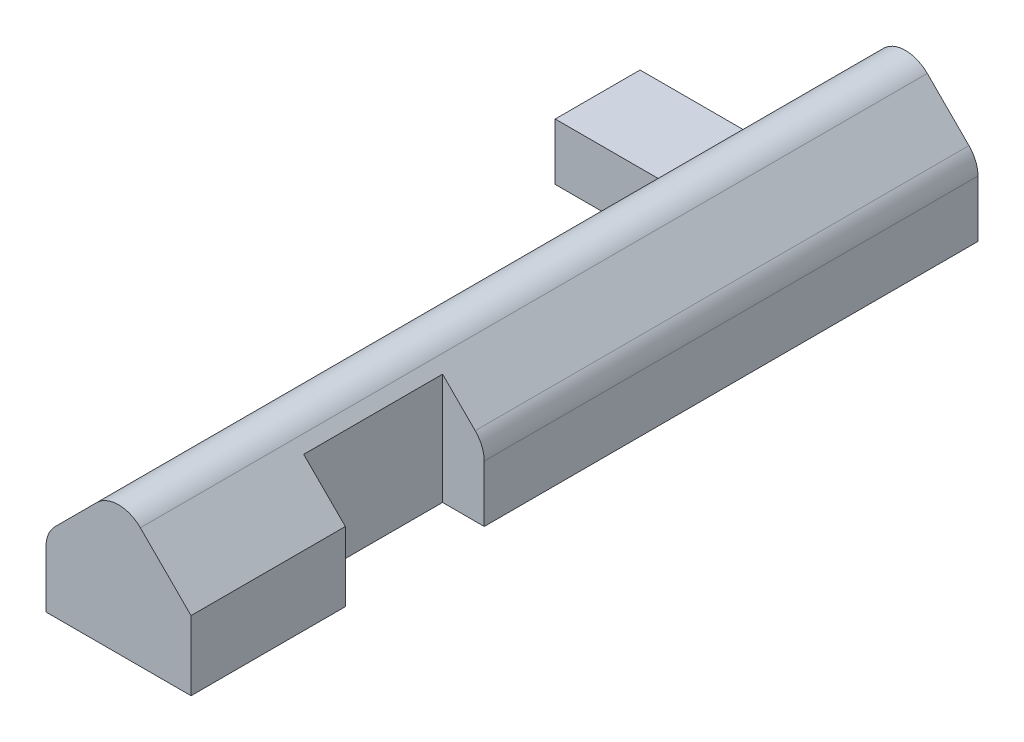
SolidWorks part; units mm, degrees
ref_plane "Płaszczyzna przednia" through (0, 0, 0) normal (0, 0, 1) x (1, 0, 0)
ref_plane "Płaszczyzna górna" through (0, 0, 0) normal (0, 1, 0) x (1, 0, 0)
ref_plane "Płaszczyzna prawa" through (0, 0, 0) normal (1, 0, 0) x (0, 0, -1)
sketch "Szkic1" plane through (0, 0, 0) normal (0, 0, 1) x (1, 0, 0)
  line L0 (0, 0) -> (0, 9.4056) construction
  line L1 (-4.7, 2.25) -> (4.7, 2.25)
  line L2 (-4.7, 2.25) -> (-4.7, -2.25)
  line L3 (-4.7, -2.25) -> (4.7, -2.25)
  line L4 (4.7, 2.25) -> (4.7, -2.25)
  line L5 (-4.7, 2.25) -> (4.7, -2.25) construction
  line L6 (-4.7, -2.25) -> (4.7, 2.25) construction
  line L7 (-4.7, 2.25) -> (0, 6.95)
  line L8 (0, 6.95) -> (4.7, 2.25)
  point P0 (0, 0)
  dimension "D1" = 9.4
  dimension "D2" = 4.5
  dimension "D3" = 45
extrude "Dodanie-wyciągnięcie1" add sketch "Szkic1" along normal blind 51 contours L8 L7 L1 | L4 L1 L2 L3
sketch "Szkic2" plane through (0, -2.25, 0) normal (0, -1, 0) x (1, 0, 0)
  line L0 (0, 0) -> (0, 51) construction
  line L1 (-4.7, 0) -> (4.7, 0) construction
  line L2 (-4.7, 51) -> (4.7, 51) construction
  line L3 (2, 41) -> (2, 32)
  line L4 (0, 32) -> (10, 32)
  line L5 (0, 32) -> (0, 41)
  line L6 (0, 41) -> (10, 41)
  line L7 (10, 32) -> (10, 41)
  line M6 (4.7, 0) -> (4.7, 51)
  dimension "D1" = 10
  dimension "D2" = 9
  dimension "D3" = 32
  dimension "D4" = 2
extrude "Wytnij-wyciągnięcie1" cut sketch "Szkic2" against normal blind 10 contours L6 L3 L4 M6 | L4 L7 L6 M6
ref_plane "Płaszczyzna1" through (-22.5, 11.75, 5) normal (0, -1, 0) x (-1, 0, 0)
sketch "Szkic4" plane through (0, -2.25, 0) normal (0, -1, 0) x (1, 0, 0)
  line L0 (0, 0) -> (0, 5) construction
  line L2 (-4.7, 0) -> (4.7, 0) construction
  line L3 (0, 0) -> (0, -7.3747) construction
  line L9 (7.5, -5) -> (-7.5, -5)
  line L10 (7.5, -5) -> (7.5, 5)
  line L11 (7.5, 5) -> (-7.5, 5)
  line L12 (-7.5, -5) -> (-7.5, 5)
  line L13 (7.5, -5) -> (-7.5, 5) construction
  line L14 (7.5, 5) -> (-7.5, -5) construction
  line L15 (13.1781, -10) -> (-13.1781, -10)
  line L16 (13.1781, -10) -> (13.1781, -5)
  line L17 (13.1781, -5) -> (-13.1781, -5)
  line L18 (-13.1781, -10) -> (-13.1781, -5)
  line L19 (13.1781, -10) -> (-13.1781, -5) construction
  line L20 (13.1781, -5) -> (-13.1781, -10) construction
  point P4 (0, 0)
  point P10 (0, -7.5)
  dimension "D1" = 5
  dimension "D2" = 15
  dimension "D3" = 10
  dimension "D4" = 5
fillet "Zaokrąglenie1" radius 2 3 edges at (4.7, 2.25, 16) (-4.7, 2.25, 25.5) (0, 6.95, 25.5)
sketch "Szkic5" plane through (0, -2.25, 0) normal (0, -1, 0) x (1, 0, 0)
  line L0 (-4.7, 51) -> (-4.7, 0) construction
  line L1 (-4.7, 5) -> (-12.2, 5)
  line L2 (-4.7, 5) -> (-4.7, 10.5)
  line L3 (-4.7, 10.5) -> (-12.2, 10.5)
  line L4 (-12.2, 5) -> (-12.2, 10.5)
  line L5 (-8.45, 10.5) -> (-8.45, 5) construction
  line L6 (-4.7, 7.75) -> (-12.2, 7.75) construction
  line L7 (-4.7, 0) -> (4.7, 0) construction
  line L8 (-4.7, 51) -> (-4.7, 0) construction
  point P196 (-8.45, 7.75)
  dimension "D1" = 5.5
  dimension "D2" = 7.5
  dimension "D3" = 5
extrude "Dodanie-wyciągnięcie4" add sketch "Szkic5" against normal up to vertex (3.6716 mm away) up to point (-4.7, 1.4216, 0)
